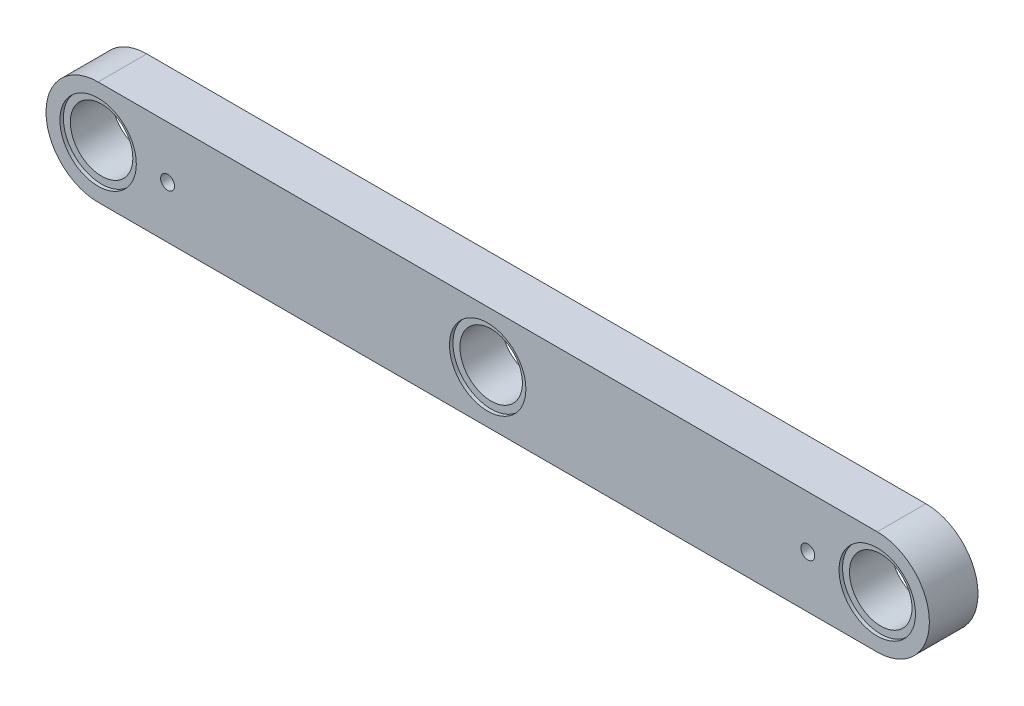
SolidWorks part; units mm, degrees
ref_plane "Front Plane" through (0, 0, 0) normal (0, 0, 1) x (1, 0, 0)
ref_plane "Top Plane" through (0, 0, 0) normal (0, 1, 0) x (1, 0, 0)
ref_plane "Right Plane" through (0, 0, 0) normal (1, 0, 0) x (0, 0, -1)
sketch "Sketch1" plane through (0, 0, 0) normal (0, 0, 1) x (1, 0, 0)
  line L0 (112.155, 0) -> (-112.155, 0) construction
  line L1 (112.155, -15) -> (-112.155, -15)
  line L2 (112.155, 15) -> (-112.155, 15)
  arc A0 (112.155, -15) -> (112.155, 15) centre (112.155, 0) ccw
  arc A1 (-112.155, 15) -> (-112.155, -15) centre (-112.155, 0) ccw
  circle A2 centre (0, 0) radius 11
  circle A3 centre (112.155, 0) radius 11
  circle A4 centre (-112.155, 0) radius 11
  circle A5 centre (-92.155, 0) radius 2
  circle A6 centre (92.155, 0) radius 2
  point P2 (0, 0)
  dimension "D1" = 22
  dimension "D2" = 15
  dimension "D4" = 4
  dimension "D5" = 20
  dimension "D3" = 224.31
  dimension "D6" = 20
extrude "Boss-Extrude1" add sketch "Sketch1" along normal mid plane 14
sketch "Sketch3" plane through (0, 0, 0) normal (0, 0, 1) x (1, 0, 0)
  circle A0 centre (112.155, 0) radius 11 construction
  circle A1 centre (0, 0) radius 11 construction
  circle A2 centre (-112.155, 0) radius 11 construction
  circle A3 centre (112.155, 0) radius 11
  circle A4 centre (0, 0) radius 11
  circle A5 centre (-112.155, 0) radius 11
  circle A6 centre (-112.155, 0) radius 9
  circle A7 centre (0, 0) radius 9
  circle A8 centre (112.155, 0) radius 9
  dimension "D1" = 18
extrude "Boss-Extrude2" add sketch "Sketch3" along normal mid plane 12
